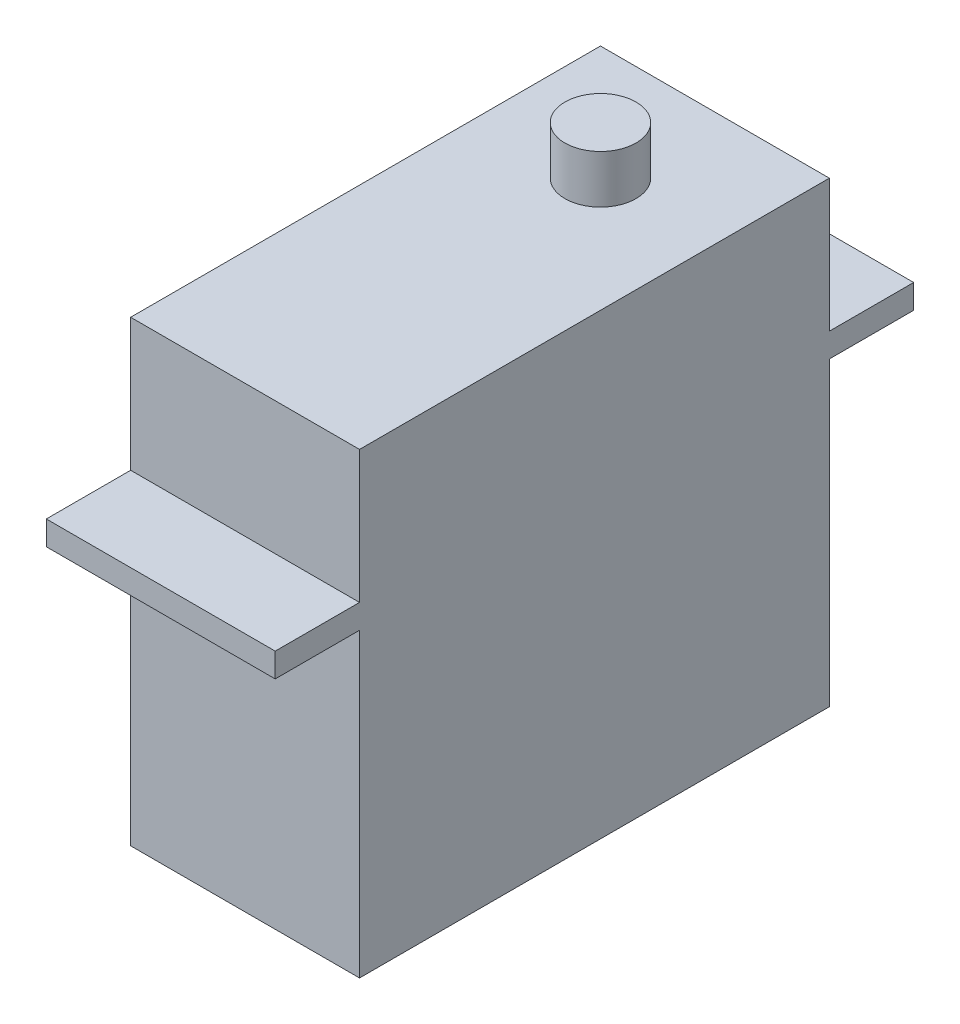
SolidWorks part; units mm, degrees
ref_plane "Plan de face" through (0, 0, 0) normal (0, 0, 1) x (1, 0, 0)
ref_plane "Plan de dessus" through (0, 0, 0) normal (0, 1, 0) x (1, 0, 0)
ref_plane "Plan de droite" through (0, 0, 0) normal (1, 0, 0) x (0, 0, -1)
sketch "Esquisse1" plane through (0, 0, 0) normal (0, 1, 0) x (1, 0, 0)
  line L1 (0, 0) -> (-19, 0)
  line L2 (0, 0) -> (0, 39)
  line L3 (0, 39) -> (-19, 39)
  line L4 (-19, 0) -> (-19, 39)
  dimension "D1" = 39
  dimension "D2" = 19
extrude "Boss.-Extru.1" add sketch "Esquisse1" along normal blind 38
sketch "Esquisse2" plane through (0, 0, -39) normal (0, 0, -1) x (-1, 0, 0)
  line L0 (0, 38) -> (0, 0) construction
  line L1 (0, 27) -> (19, 27)
  line L2 (0, 27) -> (0, 25)
  line L3 (0, 25) -> (19, 25)
  line L4 (19, 27) -> (19, 25)
  line L5 (19, 38) -> (19, 0) construction
  line L6 (0, 38) -> (19, 38) construction
  dimension "D1" = 11
  dimension "D2" = 2
extrude "Boss.-Extru.2" add sketch "Esquisse2" along normal blind 7 and the other way blind 46
sketch "Esquisse3" plane through (0, 38, 0) normal (0, 1, 0) x (1, 0, 0)
  line L0 (-19, 39) -> (-19, 0) construction
  line L1 (0, 0) -> (0, 39) construction
  line L2 (0, 39) -> (-19, 39) construction
  circle A0 centre (-9.5, 29.5) radius 9.5
  circle A1 centre (-9.5, 29.5) radius 2.95
  dimension "D1" = 5.9
extrude "Boss.-Extru.3" add sketch "Esquisse3" along normal blind 4 contours A1
